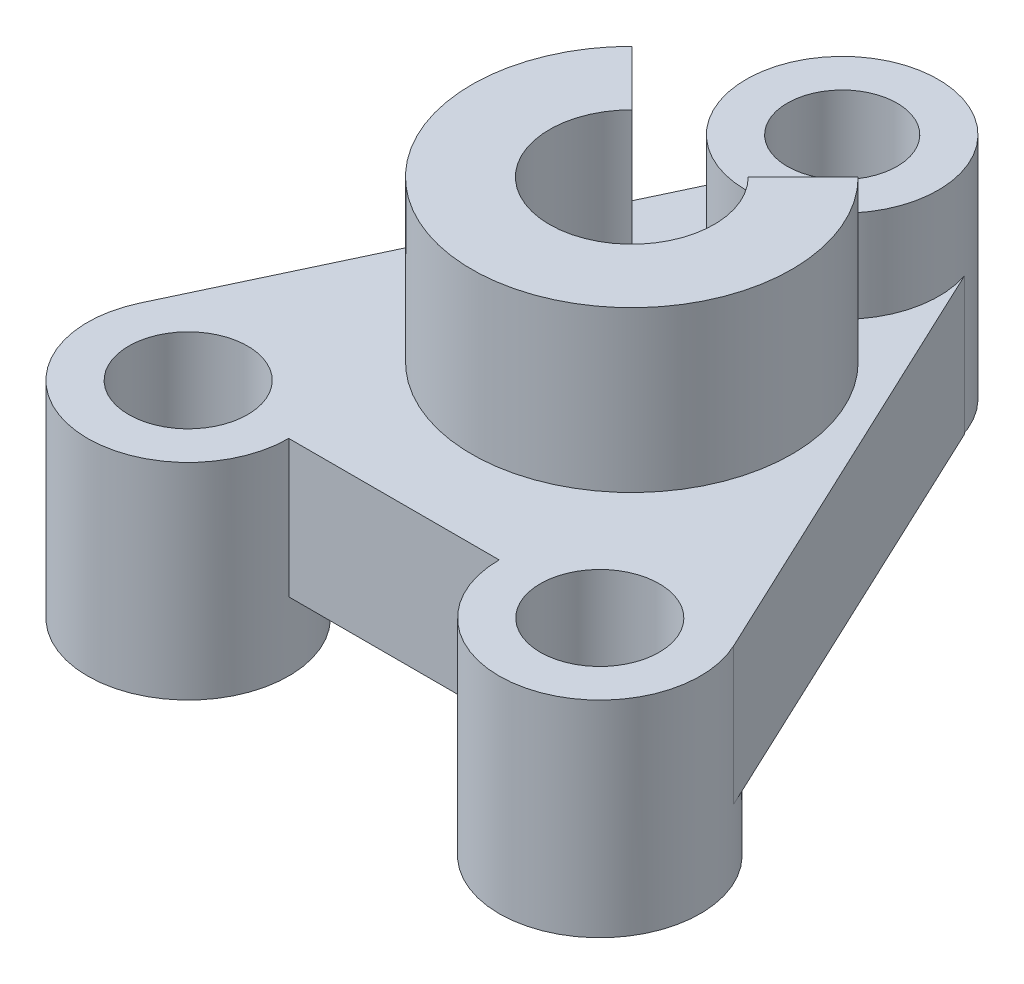
SolidWorks part; units mm, degrees
ref_plane "Front Plane" through (0, 0, 0) normal (0, 0, 1) x (1, 0, 0)
ref_plane "Top Plane" through (0, 0, 0) normal (0, 1, 0) x (1, 0, 0)
ref_plane "Right Plane" through (0, 0, 0) normal (1, 0, 0) x (0, 0, -1)
sketch "Sketch1" plane through (0, 0, 0) normal (0, 1, 0) x (1, 0, 0)
  line L0 (0, 78.9711) -> (0, -19.0289) construction
  circle A0 centre (0, 78.9711) radius 21
  circle A1 centre (0, 78.9711) radius 12
extrude "Boss-Extrude1" add sketch "Sketch1" along normal blind 50
ref_plane "Plane1" through (0, 30, 0) normal (0, 1, 0) x (1, 0, 0)
sketch "Sketch2" plane through (0, 30, 0) normal (0, 1, 0) x (1, 0, 0)
  line L0 (-64.907, -9.6635) -> (-20.0895, 85.5996)
  line L1 (0, -23.1) -> (0, 23.1) construction
  line L2 (-23, -19.0289) -> (23, -19.0289)
  line L3 (64.907, -9.6635) -> (20.0895, 85.5996)
  circle A2 centre (-45, -19.0289) radius 13
  arc A3 (-67, -19.0289) -> (-23, -19.0289) centre (-45, -19.0289) ccw
  circle A4 centre (45, -19.0289) radius 13
  arc A5 (23, -19.0289) -> (67, -19.0289) centre (45, -19.0289) ccw
  circle A6 centre (0, 78.9711) radius 12 construction
  circle A7 centre (0, 78.9711) radius 21 construction
  arc A8 (-64.907, -9.6635) -> (-23, -19.0289) centre (-45, -19.0289) ccw
  arc A9 (23, -19.0289) -> (64.907, -9.6635) centre (45, -19.0289) ccw
  arc A10 (-20.0895, 85.5996) -> (20.0895, 85.5996) centre (0, 78.9711) ccw
  circle A11 centre (-45, -19.0289) radius 22
  circle A12 centre (45, -19.0289) radius 22
  dimension "D1" = 26
  dimension "D2" = 22
  dimension "D3" = 90
  dimension "D4" = 98
extrude "Boss-Extrude2" add sketch "Sketch2" against normal blind 45 separate body contours A3 A11 A8 A2 | A9 A12 A5 A4
sketch "Sketch3" plane through (0, 30, 0) normal (0, 1, 0) x (1, 0, 0)
  line L0 (-64.907, -9.6635) -> (-20.0895, 85.5996)
  line L2 (-23, -19.0289) -> (23, -19.0289)
  line L3 (64.907, -9.6635) -> (20.0895, 85.5996)
  arc A13 (-23, -19.0289) -> (-64.907, -9.6635) centre (-45, -19.0289) ccw
  arc A14 (64.907, -9.6635) -> (23, -19.0289) centre (45, -19.0289) ccw
  arc A15 (-20.0895, 85.5996) -> (20.0895, 85.5996) centre (0, 78.9711) ccw
extrude "Boss-Extrude3" add sketch "Sketch3" against normal blind 30
ref_plane "Plane2" through (0, 65, 0) normal (0, 1, 0) x (1, 0, 0)
sketch "Sketch5" plane through (0, 65, 0) normal (0, 1, 0) x (1, 0, 0)
  line L0 (-12.7279, 45.699) -> (-24.7487, 57.7198)
  line L1 (12.7279, 45.699) -> (24.7487, 57.7198)
  arc A0 (-12.7279, 45.699) -> (12.7279, 45.699) centre (0, 32.9711) ccw
  arc A1 (-24.7487, 57.7198) -> (24.7487, 57.7198) centre (0, 32.9711) ccw
  circle A2 centre (0, 78.9711) radius 12 construction
  point P5 (0, 0)
  dimension "D1" = 36
  dimension "D2" = 70
  dimension "D3" = 46
  dimension "D4" = 90
extrude "Boss-Extrude4" add sketch "Sketch5" against normal blind 35
